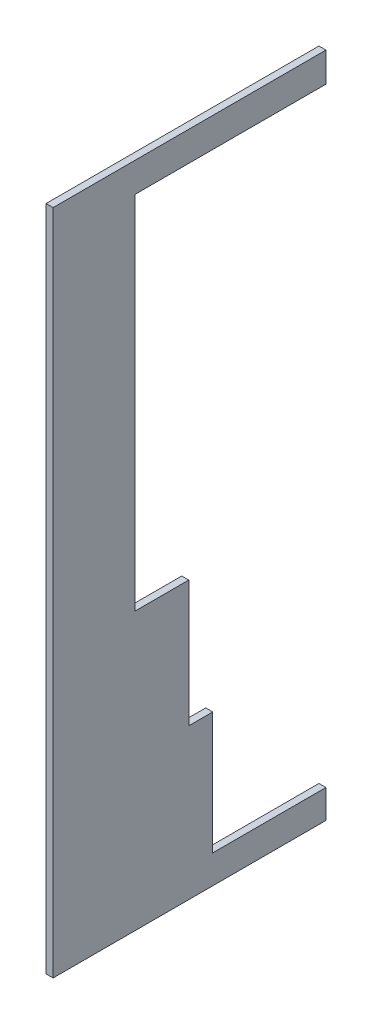
SolidWorks part; units mm, degrees
ref_plane "Спереди" through (0, 0, 0) normal (0, 0, 1) x (1, 0, 0)
ref_plane "Сверху" through (0, 0, 0) normal (0, 1, 0) x (1, 0, 0)
ref_plane "Справа" through (0, 0, 0) normal (1, 0, 0) x (0, 0, -1)
ref_plane "Плоскость4" through (0.5, 0, 0) normal (-1, 0, 0) x (0, -1, 0)
sketch "Эскиз1" plane through (0.5, 0, 0) normal (-1, 0, 0) x (0, -1, 0)
  line L0 (-5.85, 42.25) -> (-100.85, 42.25)
  line L1 (-100.85, 42.25) -> (-100.85, 3.4)
  line L2 (-100.85, 3.4) -> (-5.85, 3.4)
  line L3 (-5.85, 3.4) -> (-5.85, 42.25)
extrude "Бобышка-Вытянуть1" add sketch "Эскиз1" against normal blind 0.5
sketch "Эскиз2" plane through (0.5, 0, 0) normal (-1, 0, 0) x (0, 0, 1)
  line L0 (42.25, 5.85) -> (3.4, 5.85)
  line L1 (3.4, 5.85) -> (3.4, 100.85)
  line L2 (3.4, 100.85) -> (42.25, 100.85)
  line L3 (42.25, 100.85) -> (42.25, 5.85)
extrude "Бобышка-Вытянуть2" add sketch "Эскиз2" along normal blind 0.5
sketch "Эскиз3" plane through (0, 0, 0) normal (-1, 0, 0) x (0, 0, 1)
  line L0 (22.9259, 27.2903) -> (19.5204, 27.2903)
  line L2 (-2.7353, 45.2626) -> (-2.7353, 96.6422)
  line L3 (-2.7353, 96.6422) -> (30.5963, 96.6422)
  line L4 (30.5963, 45.2626) -> (30.5963, 96.6422)
  line L5 (19.5204, 27.2903) -> (19.5204, 9.9166)
  line L6 (19.5204, 9.9166) -> (-2.7353, 9.9166)
  line L7 (30.5963, 45.2626) -> (22.9259, 45.2626)
  line L9 (-2.7353, 45.2626) -> (-2.7353, 27.2903)
  line L11 (22.9259, 45.2626) -> (22.9259, 27.2903)
  line L12 (-2.7353, 9.9166) -> (-2.7353, 27.2903)
extrude "Вырез-Вытянуть1" cut sketch "Эскиз3" against normal through all
